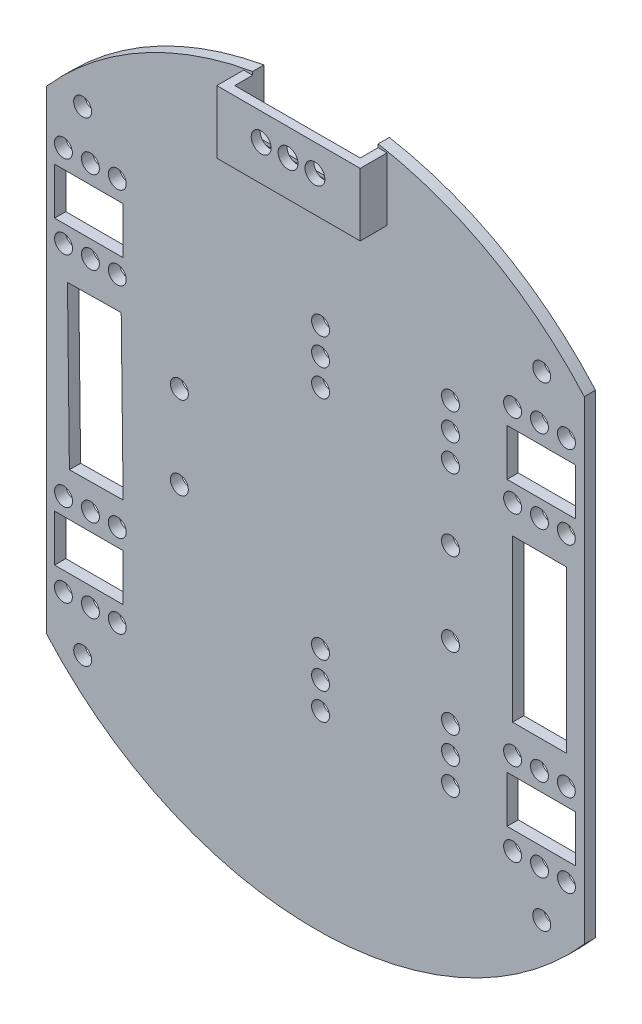
SolidWorks part; units mm, degrees
ref_plane "前基準面" through (0, 0, 0) normal (0, 0, 1) x (1, 0, 0)
ref_plane "上基準面" through (0, 0, 0) normal (0, 1, 0) x (1, 0, 0)
ref_plane "右基準面" through (0, 0, 0) normal (1, 0, 0) x (0, 0, -1)
sketch "草圖1" plane through (0, 0, 0) normal (0, 0, 1) x (1, 0, 0)
  circle A0 centre (0, 0) radius 80
  dimension "D1" = 160
extrude "填料-伸長1" add sketch "草圖1" along normal blind 2.5
sketch "草圖2" plane through (0, 0, 2.5) normal (0, 0, 1) x (1, 0, 0)
  line L1 (60, -77.1897) -> (160.6055, -77.1897)
  line L2 (160.6055, 68.5459) -> (160.6055, -77.1897)
  line L3 (60, 68.5459) -> (160.6055, 68.5459)
  line L4 (60, 68.5459) -> (60, -77.1897)
  line L5 (-60, -77.1897) -> (-160.6055, -77.1897)
  line L6 (-160.6055, 68.5459) -> (-160.6055, -77.1897)
  line L7 (-60, 68.5459) -> (-160.6055, 68.5459)
  line L8 (-60, 68.5459) -> (-60, -77.1897)
  dimension "D1" = 60
  dimension "D2" = 60
extrude "除料-伸長1" cut sketch "草圖2" against normal through all
sketch "草圖3" plane through (0, 0, 2.5) normal (0, 0, 1) x (1, 0, 0)
  circle A40 centre (50.5, 53) radius 2
  circle A41 centre (-51.9409, 53) radius 2
  circle A42 centre (50.5, -53) radius 2
  circle A43 centre (-51.9409, -53) radius 2
  dimension "D1" = 4
  dimension "D2" = 106
extrude "除料-伸長2" cut sketch "草圖3" against normal through all
sketch "草圖4" plane through (0, 0, 2.5) normal (0, 0, 1) x (1, 0, 0)
  line L1 (42.7622, 38.7409) -> (57.995, 38.7409)
  line L2 (-55.3272, 17.3351) -> (-54.8972, -18.6624)
  line L3 (42.7622, 38.7409) -> (42.7622, 28.3098)
  line L4 (42.7622, 28.3098) -> (57.995, 28.3098)
  line L5 (57.995, 38.7409) -> (57.995, 28.3098)
  line L6 (44, 18) -> (55.995, 18)
  line L7 (42.7622, -28.3098) -> (57.995, -28.3098)
  line L8 (57.995, -38.7409) -> (57.995, -28.3098)
  line L9 (42.7622, -38.7409) -> (42.7622, -28.3098)
  line L10 (42.7622, -38.7409) -> (57.995, -38.7409)
  line L11 (-58.2036, 38.7409) -> (-58.2036, 28.3098)
  line L12 (-42.9708, 28.3098) -> (-58.2036, 28.3098)
  line L13 (-42.9708, 38.7409) -> (-42.9708, 28.3098)
  line L14 (-42.9708, 38.7409) -> (-58.2036, 38.7409)
  line L15 (-42.9708, -38.7409) -> (-58.2036, -38.7409)
  line L16 (-42.9708, -38.7409) -> (-42.9708, -28.3098)
  line L17 (-58.2036, -38.7409) -> (-58.2036, -28.3098)
  line L18 (-42.9708, -28.3098) -> (-58.2036, -28.3098)
  line L19 (44, 18) -> (44, -18)
  line L20 (44, -18) -> (55.995, -18)
  line L21 (55.995, 18) -> (55.995, -18)
  line L22 (-42.903, -18.5191) -> (-54.8972, -18.6624)
  line L23 (-43.3331, 17.4783) -> (-42.903, -18.5191)
  line L24 (-43.3331, 17.4783) -> (-55.3272, 17.3351)
  circle A0 centre (56.0249, 42.9134) radius 2
  circle A1 centre (50, 42.9134) radius 2
  circle A2 centre (44, 42.9134) radius 2
  circle A3 centre (55.995, 24.4134) radius 2
  circle A4 centre (50, 24.4134) radius 2
  circle A5 centre (44, 24.4134) radius 2
  circle A6 centre (-30.3543, 9.25) radius 2
  circle A7 centre (30.1457, 9.25) radius 2
  circle A8 centre (30.1457, -9.25) radius 2
  circle A9 centre (-30.3543, -9.25) radius 2
  circle A10 centre (30.1457, -25.25) radius 2
  circle A11 centre (30.1457, -31.25) radius 2
  circle A12 centre (30.1457, -37.25) radius 2
  circle A14 centre (1.1457, 37.25) radius 2
  circle A15 centre (1.1457, 31.25) radius 2
  circle A16 centre (1.1457, 25.25) radius 2
  circle A17 centre (1.1457, -25.25) radius 2
  circle A18 centre (1.1457, -31.25) radius 2
  circle A19 centre (1.1457, -37.25) radius 2
  circle A20 centre (30.1457, 37.25) radius 2
  circle A21 centre (30.1457, 31.25) radius 2
  circle A22 centre (30.1457, 25.25) radius 2
  circle A23 centre (44, -42.9134) radius 2
  circle A24 centre (50, -42.9134) radius 2
  circle A25 centre (56.0249, -42.9134) radius 2
  circle A26 centre (55.995, -24.4134) radius 2
  circle A27 centre (50, -24.4134) radius 2
  circle A28 centre (44, -24.4134) radius 2
  circle A29 centre (-44.2086, 24.4134) radius 2
  circle A30 centre (-50.2086, 24.4134) radius 2
  circle A31 centre (-56.2036, 24.4134) radius 2
  circle A32 centre (-44.2086, 42.9134) radius 2
  circle A33 centre (-50.2086, 42.9134) radius 2
  circle A34 centre (-56.2336, 42.9134) radius 2
  circle A35 centre (-44.2086, -24.4134) radius 2
  circle A36 centre (-50.2086, -24.4134) radius 2
  circle A37 centre (-56.2036, -24.4134) radius 2
  circle A38 centre (-56.2336, -42.9134) radius 2
  circle A39 centre (-50.2086, -42.9134) radius 2
  circle A40 centre (-44.2086, -42.9134) radius 2
  point P21 (0, 0)
  dimension "D2" = 4
  dimension "D6" = 4
  dimension "D9" = 6
  dimension "D7" = 4
  dimension "D14" = 4
  dimension "D3" = 4
  dimension "D4" = 36
  dimension "D5" = 18.5
  dimension "D8" = 16
  dimension "D10" = 6
  dimension "D11" = 18
  dimension "D15" = 29
extrude "除料-伸長3" cut sketch "草圖4" against normal through all
sketch "草圖5" plane through (0, 0, 2.5) normal (0, 0, 1) x (1, 0, 0)
  line L0 (-14, 66) -> (14, 66)
  line L1 (14, 66) -> (14, 76)
  line L2 (16, 66) -> (16, 78.0293)
  line L3 (-14, 76) -> (-14, 66)
  line L4 (0, 66) -> (0, 94.9419)
  line L5 (-16, 66) -> (-16, 78.0293)
  line L6 (-16, 66) -> (-16, 64)
  line L7 (-16, 64) -> (16, 64)
  line L8 (16, 64) -> (16, 66)
  line L9 (-14, 76) -> (-14, 78.0293)
  line L10 (-14, 78.0293) -> (-16, 78.0293)
  line L11 (14, 78.0293) -> (16, 78.0293)
  line L12 (14, 78.0293) -> (14, 76)
  circle A0 centre (-0.1043, 72) radius 2.2178 construction
  dimension "D1" = 14
  dimension "D2" = 28
  dimension "D3" = 6
  dimension "D4" = 10
extrude "填料-伸長2" add sketch "草圖5" along normal blind 4 contours L11 L12 L1 L0 L3 L9 L10 L5 L6 L7 L8 L2
sketch "草圖6" plane through (0, 0, 6.5) normal (0, 0, 1) x (1, 0, 0)
  line L0 (-16, 64) -> (16, 64) construction
  line L1 (-16, 78.0293) -> (16, 78.0293)
  line L2 (-16, 78.0293) -> (-16, 64)
  line L3 (-16, 64) -> (16, 64)
  line L4 (16, 78.0293) -> (16, 64)
  line L5 (-16, 64) -> (16, 64) construction
extrude "填料-伸長3" add sketch "草圖6" along normal blind 2
sketch "草圖7" plane through (0, 0, 8.5) normal (0, 0, 1) x (1, 0, 0)
  circle A0 centre (-0.1043, 72) radius 2.2178
  circle A1 centre (5.8957, 72) radius 2.2178
  circle A2 centre (-6.1043, 72) radius 2.2178
extrude "除料-伸長4" cut sketch "草圖7" against normal blind 3
sketch "草圖8" plane through (0, 0, 0) normal (0, 0, -1) x (-1, 0, 0)
  line L0 (-16, 64) -> (-16, 78.0293) construction
  line L1 (14, 81.9515) -> (-14, 81.9515)
  line L2 (14, 81.9515) -> (14, 66.6735)
  line L3 (14, 66.6735) -> (-14, 66.6735)
  line L4 (-14, 81.9515) -> (-14, 66.6735)
  dimension "D1" = 28
  dimension "D2" = 2
extrude "除料-伸長5" cut sketch "草圖8" against normal blind 3
